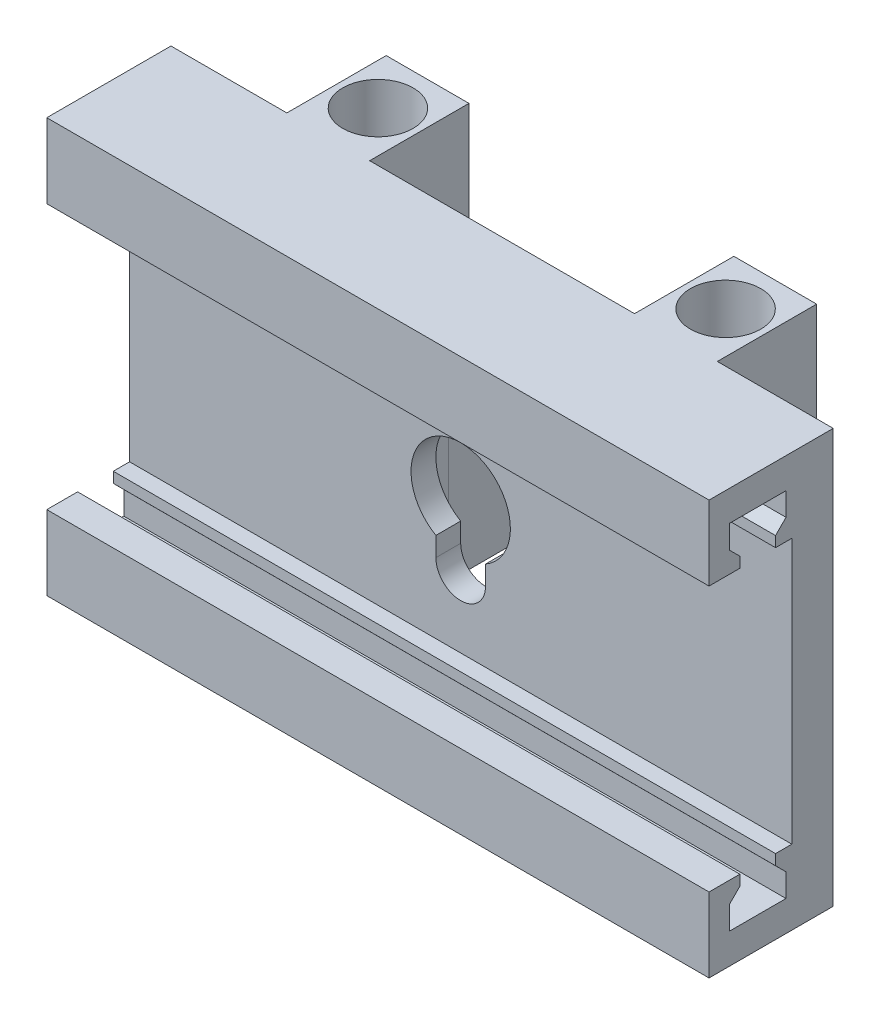
SolidWorks part; units mm, degrees
ref_plane "Front Plane" through (0, 0, 0) normal (0, 0, 1) x (1, 0, 0)
ref_plane "Top Plane" through (0, 0, 0) normal (0, 1, 0) x (1, 0, 0)
ref_plane "Right Plane" through (0, 0, 0) normal (1, 0, 0) x (0, 0, -1)
sketch "Sketch2" plane through (0, 0, 0) normal (0, 0, 1) x (1, 0, 0)
  line L0 (-40, 25) -> (40, 25)
  line L1 (-40, 25) -> (-40, -25)
  line L2 (40, 25) -> (40, -25)
  line L3 (-40, -25) -> (40, -25)
  dimension "D1" = 80
  dimension "D2" = 50
  dimension "D3" = 40
  dimension "D4" = 25
extrude "Boss-Extrude1" add sketch "Sketch2" along normal blind 5
sketch "Sketch3" plane through (0, 0, 0) normal (0, 0, -1) x (-1, 0, 0)
  line L3 (0, 0) -> (-7.9123, 0) construction
  line L7 (-3, -5.1962) -> (-3, -7.5239)
  line L8 (3, -5.1962) -> (3, -7.5239)
  arc A3 (-3, -7.5239) -> (3, -7.5239) centre (0, -7.5239) ccw
  arc A5 (-3, -5.1962) -> (3, -5.1962) centre (0, 0) cw
  dimension "D1" = 6
  dimension "D3" = 6
  dimension "D4" = 6
  dimension "D5" = 6
extrude "Cut-Extrude1" cut sketch "Sketch3" against normal blind 10
sketch "Sketch4" plane through (0, 0, 0) normal (0, 0, -1) x (-1, 0, 0)
  line L1 (-6.5, 6) -> (6.5, 6)
  line L2 (-6.5, 6) -> (-6.5, -17)
  line L3 (-6.5, -17) -> (6.5, -17)
  line L4 (6.5, 6) -> (6.5, -17)
  dimension "D4" = 6.5
  dimension "D1" = 13
  dimension "D2" = 23
  dimension "D3" = 6
extrude "Cut-Extrude2" cut sketch "Sketch4" against normal blind 2
sketch "Sketch6" plane through (0, 0, 0) normal (0, 0, -1) x (-1, 0, 0)
  line L0 (-17.6524, -5.5) -> (17.9793, -5.5) construction
  line L9 (-6.5, -17) -> (6.5, -17)
  line L10 (-6.5, -17) -> (-6.5, -21.7)
  line L11 (-6.5, -21.7) -> (6.5, -21.7)
  line L12 (6.5, -17) -> (6.5, -21.7)
  line L13 (-6.5, 6) -> (-6.5, 10.7)
  line L14 (-6.5, 10.7) -> (6.5, 10.7)
  line L15 (6.5, 6) -> (6.5, 10.7)
  line L16 (-6.5, 6) -> (6.5, 6)
  circle A2 centre (0, -19.5) radius 1.5
  circle A3 centre (0, 8.5) radius 1.5
  dimension "D8" = 3
  dimension "D1" = 11.5
  dimension "D7" = 4.7
  dimension "D9" = 2.5
extrude "Boss-Extrude2" add sketch "Sketch6" along normal blind 3
sketch "Sketch10" plane through (0, 0, 5) normal (0, 0, 1) x (1, 0, 0)
  line L0 (40, -25) -> (40, 25) construction
  line L1 (-40, 25) -> (40, 25)
  line L2 (-40, 25) -> (-40, 16)
  line L3 (-40, 16) -> (40, 16)
  line L4 (40, 25) -> (40, 16)
  line L10 (-43.9022, 0) -> (48.6041, 0) construction
  line L11 (40, -25) -> (40, -16)
  line L12 (-40, -16) -> (40, -16)
  line L13 (-40, -25) -> (-40, -16)
  line L14 (-40, -25) -> (40, -25)
  dimension "D1" = 9
extrude "Boss-Extrude5" add sketch "Sketch10" along normal blind 10
sketch "Sketch11" plane through (40, 0, 0) normal (1, 0, 0) x (0, 0, -1)
  line L0 (-11.2791, 16) -> (-11.2791, 17.27)
  line L1 (-15, 16) -> (-5, 16) construction
  line L2 (-11.2791, 17.27) -> (-12.5519, 18.5428)
  line L3 (-12.5519, 18.5428) -> (-12.5519, 21.3328)
  line L4 (-12.5519, 21.3328) -> (-5.7019, 21.3328)
  line L5 (-5.7019, 21.3328) -> (-5.7019, 18.5428)
  line L6 (-5.7019, 18.5428) -> (-6.9691, 17.27)
  line L7 (-6.9691, 17.27) -> (-6.9691, 16)
  line L8 (-11.2791, 16) -> (-6.9691, 16)
  line L9 (0, 0) -> (-21.5309, 0) construction
  line L10 (-11.2791, -16) -> (-6.9691, -16)
  line L11 (-11.2791, -16) -> (-11.2791, -17.27)
  line L12 (-11.2791, -17.27) -> (-12.5519, -18.5428)
  line L13 (-6.9691, -17.27) -> (-6.9691, -16)
  line L14 (-5.7019, -18.5428) -> (-6.9691, -17.27)
  line L15 (-5.7019, -21.3328) -> (-5.7019, -18.5428)
  line L16 (-12.5519, -18.5428) -> (-12.5519, -21.3328)
  line L17 (-12.5519, -21.3328) -> (-5.7019, -21.3328)
  dimension "D1" = 4.31
  dimension "D2" = 6.85
  dimension "D3" = 1.27
  dimension "D4" = 1.27
  dimension "D5" = 2.79
  dimension "D6" = 2.79
  dimension "D7" = 1.8
  dimension "D8" = 1.7961
extrude "Cut-Extrude3" cut sketch "Sketch11" against normal through all
sketch "Sketch13" plane through (0, 0, 0) normal (0, 0, -1) x (-1, 0, 0)
  line L0 (-40, 25) -> (40, 25) construction
  line L1 (-26, 25) -> (-16, 25)
  line L2 (-26, 25) -> (-26, -25)
  line L3 (-26, -25) -> (-16, -25)
  line L4 (-16, 25) -> (-16, -25)
  line L5 (40, -25) -> (-40, -25) construction
  line L6 (-40, -25) -> (-40, 25) construction
  line L7 (40, 25) -> (40, -25) construction
  line L8 (16, 25) -> (26, 25)
  line L9 (16, 25) -> (16, -25)
  line L10 (16, -25) -> (26, -25)
  line L11 (26, 25) -> (26, -25)
  dimension "D1" = 10
  dimension "D2" = 14
  dimension "D3" = 10
  dimension "D4" = 14
extrude "Boss-Extrude6" add sketch "Sketch13" along normal blind 12
sketch "Sketch14" plane through (0, 25, 0) normal (0, 1, 0) x (1, 0, 0)
  line L0 (0, 0) -> (0, 21.6762) construction
  line L9 (16, 0) -> (-16, 0) construction
  line L14 (-16, 12) -> (-16, 0) construction
  line L16 (-26, 0) -> (-40, 0) construction
  circle A1 centre (-21, 6) radius 4.25
  circle A2 centre (21, 6) radius 4.25
  dimension "D1" = 8.5
  dimension "D2" = 8.5
  dimension "D3" = 6
  dimension "D5" = 5
extrude "Cut-Extrude4" cut sketch "Sketch14" against normal through all
sketch "Sketch17" plane through (0, 0, 0) normal (0, 0, -1) x (-1, 0, 0)
  line L0 (0, 25) -> (0, -25) construction
  line L1 (-16, 25) -> (16, 25) construction
  line L2 (16, -25) -> (-16, -25) construction
  line L4 (6.5367, -14.3094) -> (13.4741, -14.3094)
  line L5 (6.5367, -14.3094) -> (6.5367, 6)
  line L6 (6.5367, 6) -> (13.4741, 6)
  line L7 (13.4741, -14.3094) -> (13.4741, 6)
  line L8 (-6.5367, -14.3094) -> (-13.4741, -14.3094)
  line L9 (-6.5367, 6) -> (-13.4741, 6)
  line L10 (-13.4741, -14.3094) -> (-13.4741, 6)
  line L11 (-6.5367, -14.3094) -> (-6.5367, 6)
  point P16 (0, 0)
extrude "Boss-Extrude7" add sketch "Sketch17" along normal blind 10
sketch "Sketch18" plane through (0, 6, 0) normal (0, 1, 0) x (1, 0, 0)
  line L1 (7.3693, 9.2172) -> (12.6913, 9.2172)
  line L2 (7.3693, 9.2172) -> (7.3693, 0.005)
  line L3 (7.3693, 0.005) -> (12.6913, 0.005)
  line L4 (12.6913, 9.2172) -> (12.6913, 0.005)
  line L9 (-12.3101, 7.89) -> (-9.3101, 7.89)
  line L10 (-12.3101, 7.89) -> (-12.3101, 2.39)
  line L11 (-12.3101, 2.39) -> (-9.3101, 2.39)
  line L12 (-9.3101, 7.89) -> (-9.3101, 2.39)
  dimension "D1" = 3
  dimension "D2" = 5.5
extrude "Cut-Extrude5" cut sketch "Sketch18" against normal through all
